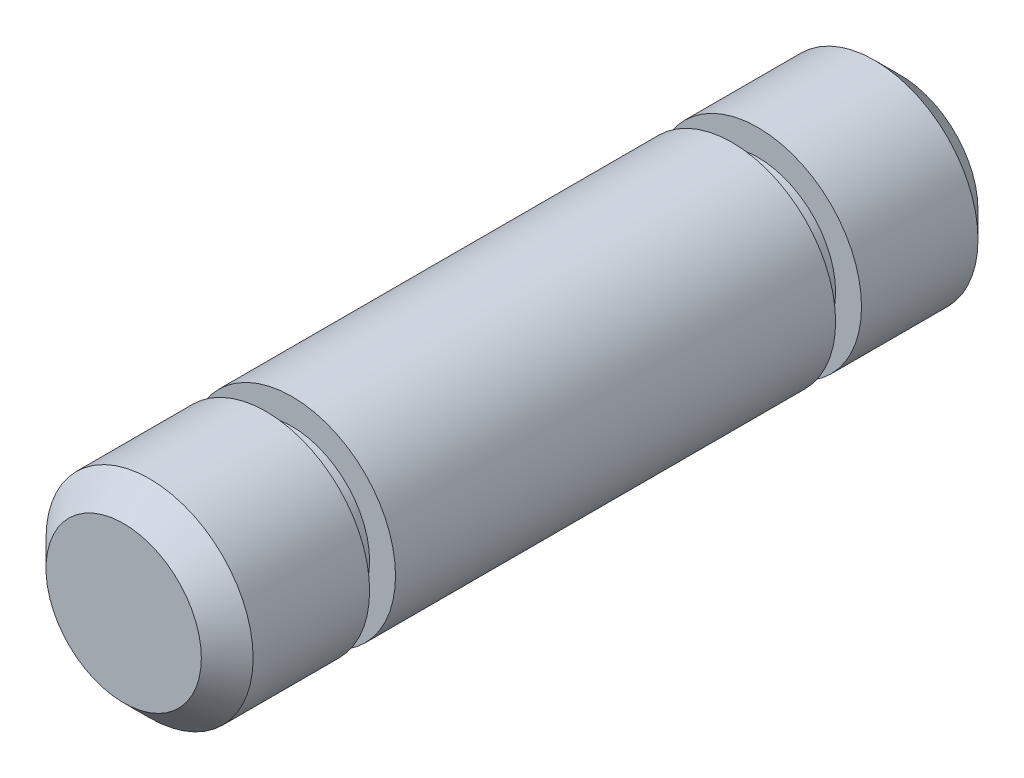
SolidWorks part; units mm, degrees
ref_plane "前视基准面" through (0, 0, 0) normal (0, 0, 1) x (1, 0, 0)
ref_plane "上视基准面" through (0, 0, 0) normal (0, 1, 0) x (1, 0, 0)
ref_plane "右视基准面" through (0, 0, 0) normal (1, 0, 0) x (0, 0, -1)
other "Configuration Table"
sketch "草图1" plane through (0, 0, 0) normal (0, 0, 1) x (1, 0, 0)
  circle A0 centre (0, 0) radius 8
extrude "凸台-拉伸1" add sketch "草图1" along normal blind 60
chamfer "倒角1" distance 2 angle 45 2 edges at (8, 0, 0) (8, 0, 60)
ref_plane "基准面1" through (0, 0, 13) normal (0, 0, 1) x (1, 0, 0)
sketch "草图3" plane through (0, 0, 13) normal (0, 0, 1) x (1, 0, 0)
  circle A0 centre (0, 0) radius 6
extrude "切除-拉伸1" cut sketch "草图3" against normal blind 2 flip side to cut
ref_plane "基准面2" through (0, 0, 47) normal (0, 0, 1) x (1, 0, 0)
sketch "草图4" plane through (0, 0, 47) normal (0, 0, 1) x (1, 0, 0)
  circle A0 centre (0, 0) radius 6
extrude "切除-拉伸2" cut sketch "草图4" along normal blind 2 flip side to cut
